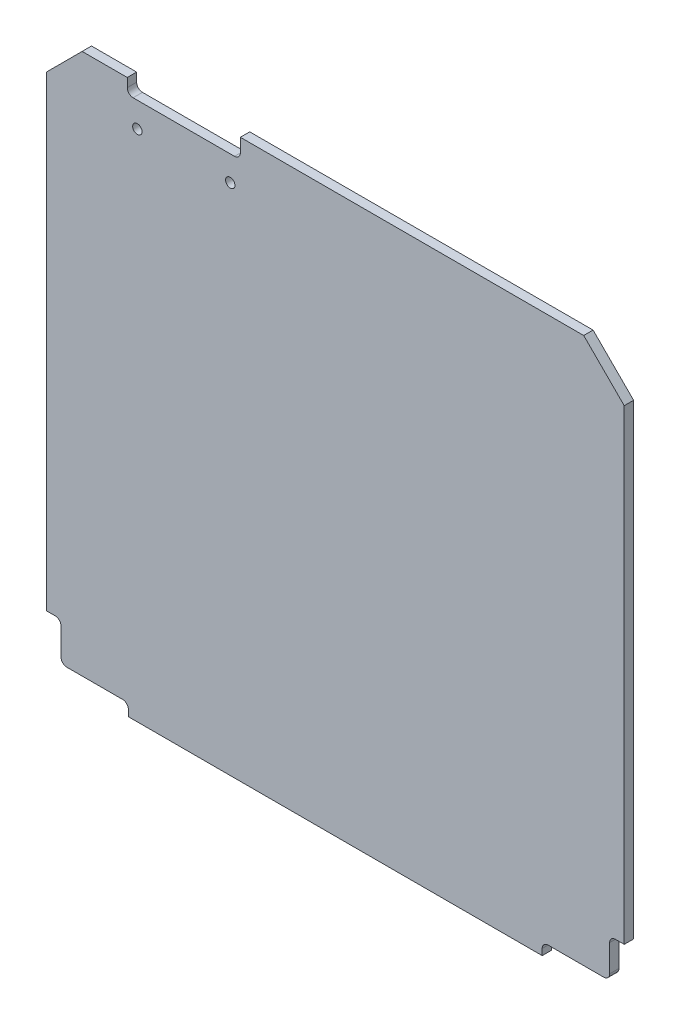
SolidWorks part; units mm, degrees
ref_plane "Front Plane" through (0, 0, 0) normal (0, 0, 1) x (1, 0, 0)
ref_plane "Top Plane" through (0, 0, 0) normal (0, 1, 0) x (1, 0, 0)
ref_plane "Right Plane" through (0, 0, 0) normal (1, 0, 0) x (0, 0, -1)
ref_plane "Plane1" through (0, 0, 1.5875) normal (0, 0, 1) x (1, 0, 0)
sketch "Sketch1" plane through (0, 0, 1.5875) normal (0, 0, 1) x (1, 0, 0)
  line L0 (-35.3, -48) -> (-35.3, -49.065)
  line L1 (-35.3, -49.065) -> (35.3, -49.065)
  line L2 (35.3, -49.065) -> (35.3, -48)
  line L3 (36.3, -47) -> (45.8, -47)
  line L4 (46.8, -46) -> (46.8, -41.4)
  line L5 (47.8, -40.4) -> (49.3, -40.4)
  line L6 (49.3, -40.4) -> (49.3, 39.2)
  line L7 (49.3, 39.2) -> (42.385, 46.115)
  line L8 (42.385, 46.115) -> (-16.2, 46.115)
  line L9 (-16.2, 46.115) -> (-16.2, 43.8)
  line L10 (-17.2, 42.8) -> (-34.5, 42.8)
  line L11 (-35.5, 43.8) -> (-35.5, 45.3)
  line L12 (-35.5, 45.3) -> (-43.2, 45.3)
  line L13 (-43.2, 45.3) -> (-49.3, 39.2)
  line L14 (-49.3, 39.2) -> (-49.3, -40.4)
  line L15 (-49.3, -40.4) -> (-47.8, -40.4)
  line L16 (-46.8, -41.4) -> (-46.8, -46)
  line L17 (-45.8, -47) -> (-36.3, -47)
  arc A0 (-36.3, -47) -> (-35.3, -48) centre (-36.3, -48) cw
  arc A1 (35.3, -48) -> (36.3, -47) centre (36.3, -48) cw
  arc A2 (45.8, -47) -> (46.8, -46) centre (45.8, -46) ccw
  arc A3 (46.8, -41.4) -> (47.8, -40.4) centre (47.8, -41.4) cw
  arc A4 (-16.2, 43.8) -> (-17.2, 42.8) centre (-17.2, 43.8) cw
  arc A5 (-34.5, 42.8) -> (-35.5, 43.8) centre (-34.5, 43.8) cw
  arc A6 (-47.8, -40.4) -> (-46.8, -41.4) centre (-47.8, -41.4) cw
  arc A7 (-46.8, -46) -> (-45.8, -47) centre (-45.8, -46) ccw
  circle A8 centre (-17.925, 38.5406) radius 0.8
  circle A9 centre (-33.775, 38.54) radius 0.8
  point P38 (0, 0)
  point P39 (42.385, 46.115)
  point P40 (42.385, 46.115)
extrude "Boss-Extrude1" add sketch "Sketch1" against normal blind 1.6
